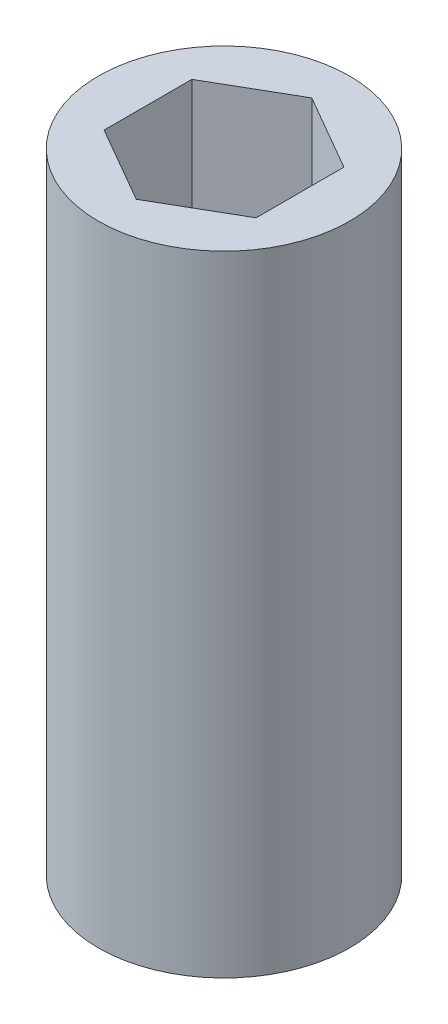
SolidWorks part; units mm, degrees
ref_plane "Front Plane" through (0, 0, 0) normal (0, 0, 1) x (1, 0, 0)
ref_plane "Top Plane" through (0, 0, 0) normal (0, 1, 0) x (1, 0, 0)
ref_plane "Right Plane" through (0, 0, 0) normal (1, 0, 0) x (0, 0, -1)
sketch "Sketch1" plane through (0, 0, 0) normal (0, 1, 0) x (1, 0, 0)
  line L1 (0, 5.5433) -> (-4.8006, 2.7716)
  line L2 (-4.8006, 2.7716) -> (-4.8006, -2.7716)
  line L3 (-4.8006, -2.7716) -> (0, -5.5433)
  line L4 (0, -5.5433) -> (4.8006, -2.7716)
  line L5 (4.8006, -2.7716) -> (4.8006, 2.7716)
  line L6 (4.8006, 2.7716) -> (0, 5.5433)
  circle A0 centre (0, 0) radius 7.9375
  circle A1 centre (0, 0) radius 4.8006 construction
  dimension "D1" = 9.6012
  dimension "D2" = 15.875
extrude "Boss-Extrude1" add sketch "Sketch1" along normal blind 39.751
